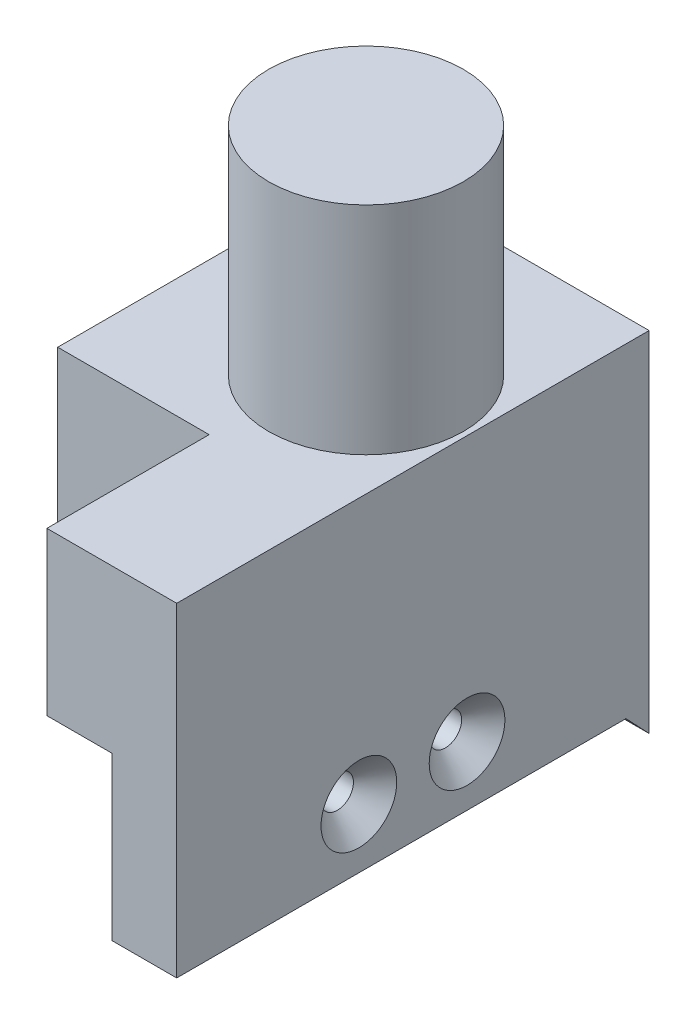
SolidWorks part; units mm, degrees
material "ABS"
ref_plane "Спереди" through (0, 0, 0) normal (0, 0, 1) x (1, 0, 0)
ref_plane "Сверху" through (0, 0, 0) normal (0, 1, 0) x (1, 0, 0)
ref_plane "Справа" through (0, 0, 0) normal (1, 0, 0) x (0, 0, -1)
sketch "Эскиз1" plane through (0, 0, 0) normal (0, 1, 0) x (1, 0, 0)
  circle A0 centre (0, 0) radius 9
  dimension "D1" = 18
extrude "Бобышка-Вытянуть1" add sketch "Эскиз1" along normal blind 20
sketch "Эскиз2" plane through (0, 0, 0) normal (0, -1, 0) x (1, 0, 0)
  line L0 (-6.5, 21) -> (-6.5, 5.165) construction
  line L1 (3.5, -16.67) -> (-16.5, -16.67)
  line L2 (3.5, -16.67) -> (3.5, 27)
  line L3 (3.5, 27) -> (-16.5, 27)
  line L4 (-16.5, -16.67) -> (-16.5, 27)
  line L5 (3.5, -16.67) -> (-16.5, 27) construction
  line L6 (3.5, 27) -> (-16.5, -16.67) construction
  circle A0 centre (-6.5, 21) radius 3 construction
  point P0 (-6.5, 5.165)
  dimension "D6" = 6
  dimension "D1" = 43.67
  dimension "D2" = 20
  dimension "D3" = 6
  dimension "D4" = 6.5
  dimension "D5" = 21
extrude "Бобышка-Вытянуть2" add sketch "Эскиз2" along normal blind 15
sketch "Эскиз3" plane through (0, 0, 0) normal (0, 1, 0) x (1, 0, 0)
  line L0 (-16.5, -27) -> (-16.5, 16.67) construction
  line L1 (-16.5, -27) -> (-16.5, -12)
  line L2 (3.5, -27) -> (-16.5, -27) construction
  line L3 (-2.5, -27) -> (-16.5, -27)
  line L4 (-2.5, -27) -> (-2.5, -12)
  line L5 (-2.5, -12) -> (-16.5, -12)
  line L6 (3.5, -8.2916) -> (3.5, -27) construction
  dimension "D1" = 6
  dimension "D2" = 15
extrude "Вырез-Вытянуть1" cut sketch "Эскиз3" against normal through all
sketch "Эскиз4" plane through (0, -15, 0) normal (0, -1, 0) x (1, 0, 0)
  line L0 (3.5, -16.67) -> (3.5, 27) construction
  line L1 (-16.5, -16.67) -> (3.5, -16.67)
  line L2 (-16.5, -16.67) -> (-16.5, -12.67)
  line L3 (-16.5, -12.67) -> (3.5, -12.67)
  line L4 (3.5, -16.67) -> (3.5, -12.67)
  dimension "D1" = 4
extrude "Бобышка-Вытянуть3" add sketch "Эскиз4" along normal blind 17.26
sketch "Эскиз5" plane through (-16.5, 0, 0) normal (-1, 0, 0) x (0, 0, 1)
  line L0 (-12.67, -32.26) -> (-12.67, -15) construction
  line L1 (-12.67, -32.26) -> (-12.67, -28.0316)
  line L2 (-12.67, -32.26) -> (-16.67, -32.26) construction
  line L3 (-12.67, -32.26) -> (-16.67, -32.26)
  line L4 (-12.67, -28.0316) -> (-16.67, -32.26)
  line L5 (-16.67, -32.26) -> (-16.67, 0) construction
  dimension "D1" = 43.41
extrude "Вырез-Вытянуть2" cut sketch "Эскиз5" against normal through all
sketch "Эскиз6" plane through (0, 0, 0) normal (0, -1, 0) x (1, 0, 0)
  line L0 (3.5, 8.2916) -> (3.5, 27) construction
  line L1 (3.5, 8.2916) -> (3.5, 27)
  line L2 (3.5, -8.2916) -> (3.5, 8.2916) construction
  line L3 (3.5, -8.2916) -> (3.5, 8.2916)
  line L4 (3.5, -16.67) -> (3.5, -8.2916) construction
  line L5 (3.5, -16.67) -> (3.5, -8.2916)
  line L6 (3.5, 27) -> (9.5, 27)
  line L7 (9.5, 27) -> (9.5, -16.67)
  line L8 (9.5, -16.67) -> (3.5, -16.67)
  dimension "D1" = 6
extrude "Бобышка-Вытянуть4" add sketch "Эскиз6" along normal blind 30
sketch "Эскиз7" plane through (9.5, 0, 0) normal (1, 0, 0) x (0, 0, -1)
  line L0 (-27, -24.5) -> (16.67, -24.5) construction
  line L1 (-27, -30) -> (-27, 0) construction
  line L2 (16.67, -30) -> (16.67, 0) construction
  line L3 (16.67, 0) -> (-27, 0) construction
  circle A0 centre (-10.16, -24.5) radius 1.5
  circle A1 centre (-0.16, -24.5) radius 1.5
  dimension "D2" = 3
  dimension "D1" = 10
  dimension "D3" = 16.84
  dimension "D4" = 24.5
extrude "Вырез-Вытянуть3" cut sketch "Эскиз7" against normal through all
sketch "Эскиз8" plane through (3.5, 0, 0) normal (1, 0, 0) x (0, 0, -1)
  line L3 (16.67, -30) -> (14.5321, -30)
  line L4 (14.5321, -30) -> (16.67, -32.26)
  line L5 (16.67, -32.26) -> (16.67, -30)
  line L6 (16.67, -30) -> (14.5321, -30)
  line L7 (14.5321, -30) -> (16.67, -32.26)
  line L8 (16.67, -32.26) -> (16.67, -30)
  dimension "D1" = 0
extrude "Бобышка-Вытянуть5" add sketch "Эскиз8" along normal up to surface (6 mm away) up to face at (9.5, -24.5, -1.34)
chamfer "Фаска1" distance 2 angle 45 2 edges at (9.5, -24.5, -1.34) (9.5, -24.5, 8.66)
